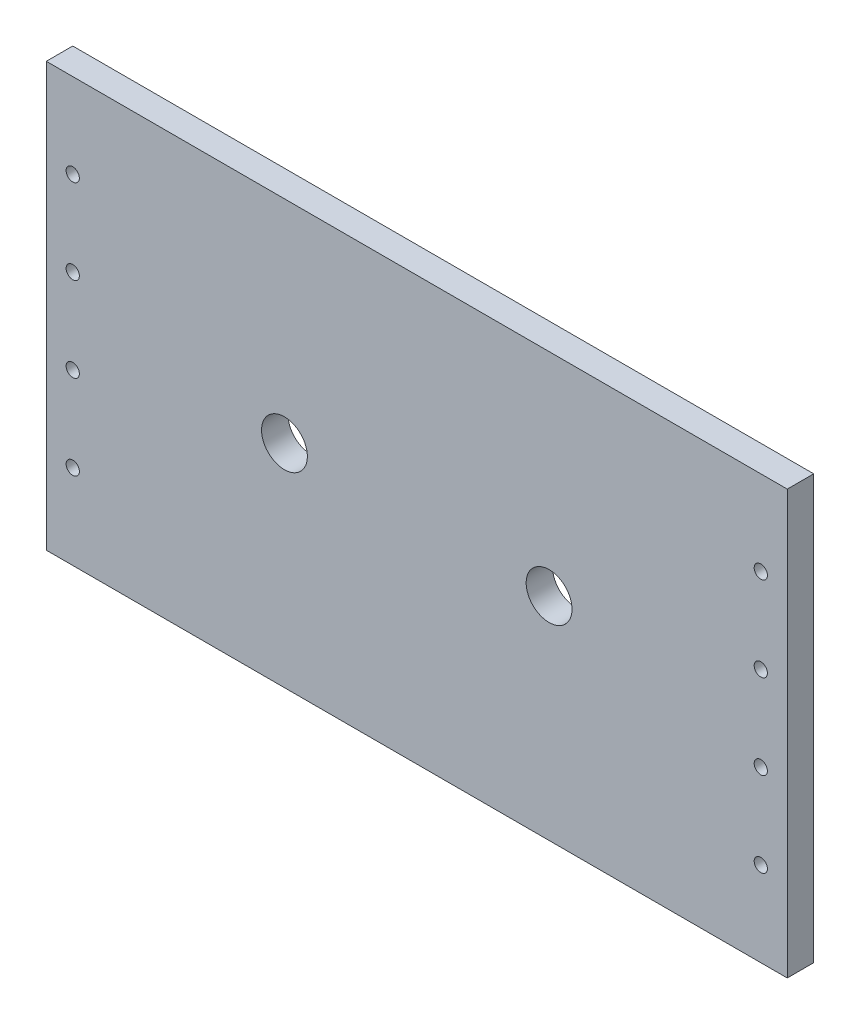
SolidWorks part; units mm, degrees
material "ABS"
ref_plane "Front Plane" through (0, 0, 0) normal (0, 0, 1) x (1, 0, 0)
ref_plane "Top Plane" through (0, 0, 0) normal (0, 1, 0) x (1, 0, 0)
ref_plane "Right Plane" through (0, 0, 0) normal (1, 0, 0) x (0, 0, -1)
sketch "Sketch1" plane through (0, 0, 0) normal (0, 0, 1) x (1, 0, 0)
  line L1 (0, 0) -> (177.8, 0)
  line L2 (0, 0) -> (0, 101.6)
  line L3 (0, 101.6) -> (177.8, 101.6)
  line L4 (177.8, 0) -> (177.8, 101.6)
  dimension "D1" = 101.6
  dimension "D2" = 177.8
extrude "Boss-Extrude1" add sketch "Sketch1" along normal blind 6.35
sketch "Sketch2" plane through (0, 0, 6.35) normal (0, 0, 1) x (1, 0, 0)
  line L0 (0, 0) -> (177.8, 0) construction
  line L1 (177.8, 101.6) -> (0, 101.6) construction
  line L3 (0, 101.6) -> (0, 0) construction
  line L4 (177.8, 0) -> (177.8, 101.6) construction
  circle A0 centre (6.35, 81.28) radius 1.5875
  circle A1 centre (6.35, 60.96) radius 1.5875
  circle A2 centre (6.35, 40.64) radius 1.5875
  circle A3 centre (6.35, 20.32) radius 1.5875
  circle A4 centre (171.45, 20.32) radius 1.5875
  circle A5 centre (171.45, 40.64) radius 1.5875
  circle A6 centre (171.45, 60.96) radius 1.5875
  circle A7 centre (171.45, 81.28) radius 1.5875
  dimension "D1" = 3.175
  dimension "D2" = 20.32
  dimension "D3" = 20.32
  dimension "D4" = 20.32
  dimension "D5" = 20.32
  dimension "D6" = 6.35
  dimension "D7" = 6.35
extrude "Cut-Extrude1" cut sketch "Sketch2" against normal blind 6.35
sketch "Sketch5" plane through (0, 0, 6.35) normal (0, 0, 1) x (1, 0, 0)
  line L0 (177.8, 101.6) -> (0, 101.6) construction
  line L13 (0, 101.6) -> (0, 0) construction
  circle A0 centre (120.65, 50.8) radius 5.4993
  circle A2 centre (57.15, 50.8) radius 5.4993
  dimension "D1" = 10.9985
  dimension "D2" = 50.8
  dimension "D3" = 57.15
  dimension "D4" = 63.5
extrude "Cut-Extrude3" cut sketch "Sketch5" against normal blind 6.35
